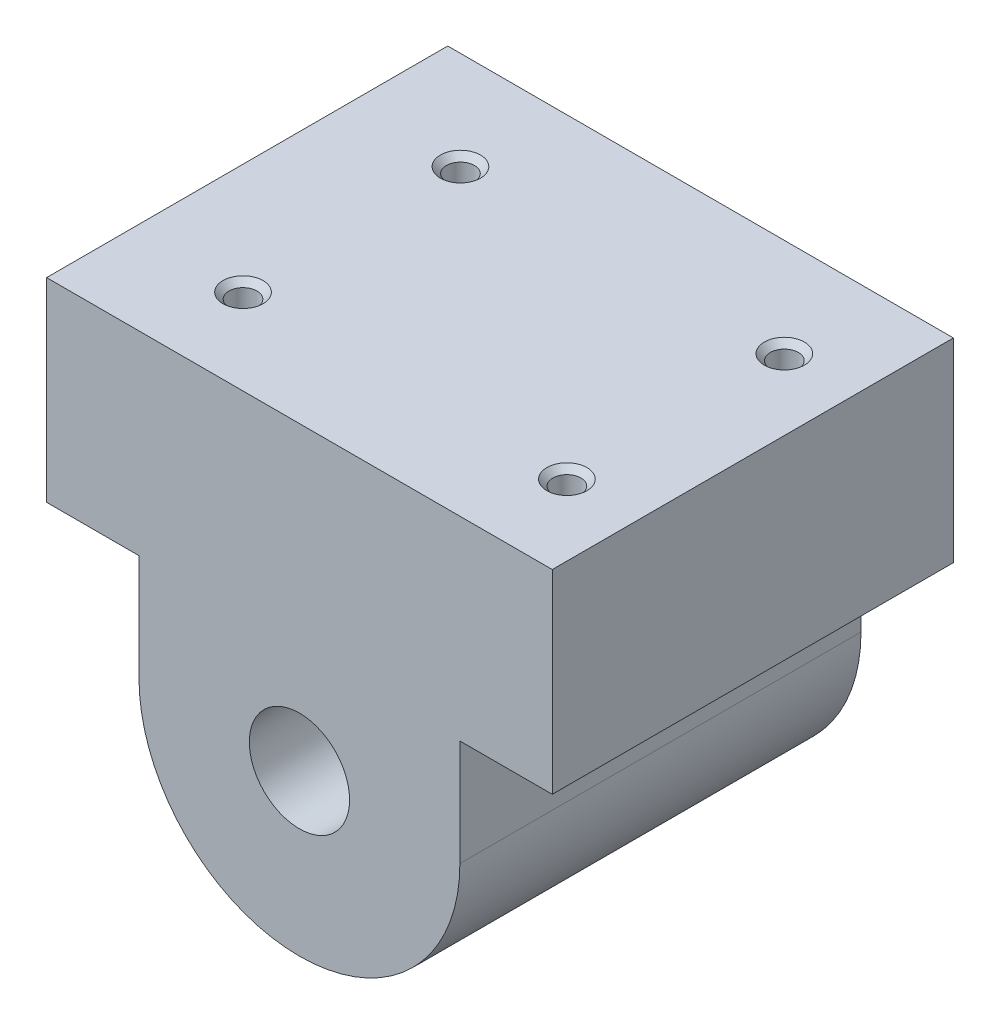
SolidWorks part; units mm, degrees
ref_plane "前视基准面" through (0, 0, 0) normal (0, 0, 1) x (1, 0, 0)
ref_plane "上视基准面" through (0, 0, 0) normal (0, 1, 0) x (1, 0, 0)
ref_plane "右视基准面" through (0, 0, 0) normal (1, 0, 0) x (0, 0, -1)
ref_plane "基准面4" through (0, 0, 100) normal (0, 0, 1) x (1, 0, 0)
sketch "草图1" plane through (0, 0, 100) normal (0, 0, 1) x (1, 0, 0)
  line L0 (80, 0) -> (80, 150)
  line L1 (80, 150) -> (-80, 150)
  line L2 (-80, 150) -> (-80, 0)
  arc A0 (-80, 0) -> (80, 0) centre (0, 0) ccw
extrude "凸台-拉伸1" add sketch "草图1" against normal blind 200
sketch "草图2" plane through (80, 0, 0) normal (1, 0, 0) x (0, 0, -1)
  line L0 (-100, 150) -> (100, 150)
  line L1 (100, 150) -> (100, 52.9426)
  line L2 (100, 52.9426) -> (-100, 52.9426)
  line L3 (-100, 52.9426) -> (-100, 150)
extrude "凸台-拉伸2" add sketch "草图2" along normal blind 46.0614
sketch "草图3" plane through (-80, 0, 0) normal (-1, 0, 0) x (0, 0, 1)
  line L0 (100, 52.9426) -> (-100, 52.9426)
  line L1 (-100, 52.9426) -> (-100, 150)
  line L2 (-100, 150) -> (100, 150)
  line L3 (100, 150) -> (100, 52.9426)
extrude "凸台-拉伸3" add sketch "草图3" along normal blind 46.0614
hole_wizard "孔1" positions "草图5" profile "草图4" legacy
sketch "草图5" plane through (0, 0, 100) normal (0, 0, 1) x (1, 0, 0)
  point P0 (0, 0)
sketch "草图4" plane through (0, 0, 100) normal (1, 0, 0) x (0, -1, 0)
  line L0 (0, 0) -> (0, 200)
  line L1 (0, 200) -> (25, 200)
  line L2 (25, 200) -> (25, 0)
  line L3 (25, 0) -> (0, 0)
  line L4 (0, 110) -> (0, -10) construction
  dimension "直径" = 50
  dimension "深度" = 200
hole_wizard "孔2" positions "草图7" profile "草图6" legacy
sketch "草图7" plane through (0, 150, 0) normal (0, 1, 0) x (1, 0, 0)
  point P0 (-70.811, 51.0912)
  point P1 (-70.811, -57.3206)
  point P2 (90.6852, -57.3206)
  point P3 (90.6852, 51.0912)
sketch "草图6" plane through (-70.811, 150, -51.0912) normal (1, 0, 0) x (0, 0, 1)
  line L0 (0, 0) -> (0, 34.206)
  line L1 (0, 34.206) -> (7, 30)
  line L2 (7, 30) -> (7, 0)
  line L4 (7, 0) -> (0, 0)
  line L6 (0, 34.206) -> (-7, 30) construction
  line L7 (0, -4.2442) -> (0, 117.3081) construction
  dimension "直径" = 14
  dimension "深度" = 30
  dimension "导头角度" = 118
chamfer "倒角1" distance 3 angle 45 4 edges at (90.6852, 150, -44.0912) (90.6852, 150, 64.3206) (-70.811, 150, -44.0912) (-70.811, 150, 64.3206)
